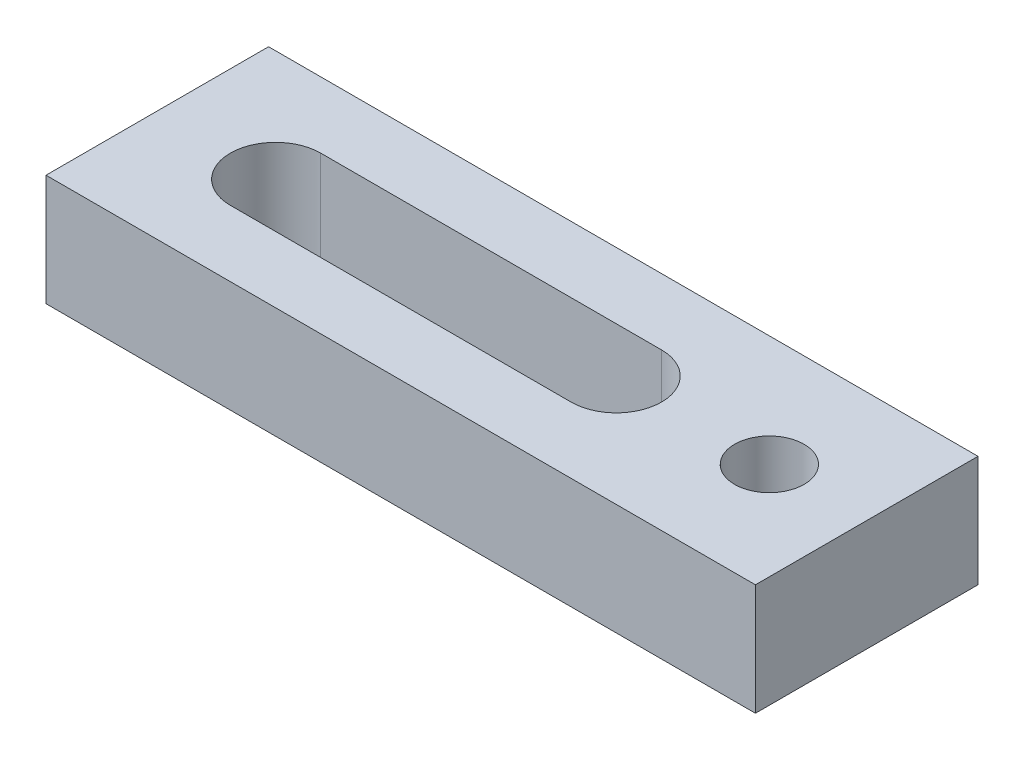
SolidWorks part; units mm, degrees
ref_plane "Alzado" through (0, 0, 0) normal (0, 0, 1) x (1, 0, 0)
ref_plane "Planta" through (0, 0, 0) normal (0, 1, 0) x (1, 0, 0)
ref_plane "Vista lateral" through (0, 0, 0) normal (1, 0, 0) x (0, 0, -1)
sketch "Croquis3" plane through (0, 0, 0) normal (0, 1, 0) x (1, 0, 0)
  line L1 (0, 0) -> (51, 0)
  line L2 (0, 0) -> (0, 16)
  line L3 (0, 16) -> (51, 16)
  line L4 (51, 0) -> (51, 16)
  dimension "D1" = 16
  dimension "D2" = 51
extrude "Saliente-Extruir1" add sketch "Croquis3" along normal blind 8 contours L1 L4 L3 L2
sketch "Croquis5" plane through (0, 8, 0) normal (0, 1, 0) x (1, 0, 0)
  line L0 (8.5, 8) -> (33, 8) construction
  line L1 (8.5, 11.25) -> (33, 11.25)
  line L2 (8.5, 4.75) -> (33, 4.75)
  line L3 (0, 0) -> (51, 0) construction
  line L4 (0, 0) -> (0, 16) construction
  line L6 (51, 0) -> (51, 16) construction
  arc A0 (8.5, 11.25) -> (8.5, 4.75) centre (8.5, 8) ccw
  arc A1 (33, 4.75) -> (33, 11.25) centre (33, 8) ccw
  circle A2 centre (44, 8) radius 2.5
  point P2 (20.75, 8)
  point P17 (5.25, 8)
  point P18 (36.25, 8)
  dimension "D3" = 5
  dimension "D1" = 8
  dimension "D2" = 7
  dimension "D4" = 8
  dimension "D5" = 8.5
  dimension "D6" = 6.5
  dimension "D7" = 31
sketch "Croquis15" plane through (0, 8, 0) normal (0, 1, 0) x (1, 0, 0)
  line L0 (8.5, 8) -> (33, 8) construction
  line L1 (8.5, 11.25) -> (33, 11.25)
  line L2 (8.5, 4.75) -> (33, 4.75)
  line L3 (0, 0) -> (51, 0) construction
  line L6 (0, 0) -> (0, 16) construction
  arc A0 (8.5, 11.25) -> (8.5, 4.75) centre (8.5, 8) ccw
  arc A1 (33, 4.75) -> (33, 11.25) centre (33, 8) ccw
  point P2 (20.75, 8)
  point P11 (0, 8)
  point P12 (5.25, 8)
  point P13 (36.25, 8)
  dimension "D1" = 8
  dimension "D2" = 8.5
  dimension "D3" = 6.5
  dimension "D4" = 31
extrude "Cortar-Extruir4" cut sketch "Croquis15" against normal through all contours L1 A1 L2 A0
sketch "Croquis32" plane through (0, 8, 0) normal (0, 1, 0) x (1, 0, 0)
  line L0 (51, 0) -> (51, 16) construction
  line L1 (0, 0) -> (51, 0) construction
  circle A0 centre (44, 8) radius 2.5
  dimension "D1" = 5
  dimension "D2" = 7
  dimension "D3" = 8
extrude "Cortar-Extruir6" cut sketch "Croquis32" against normal through all contours A0
